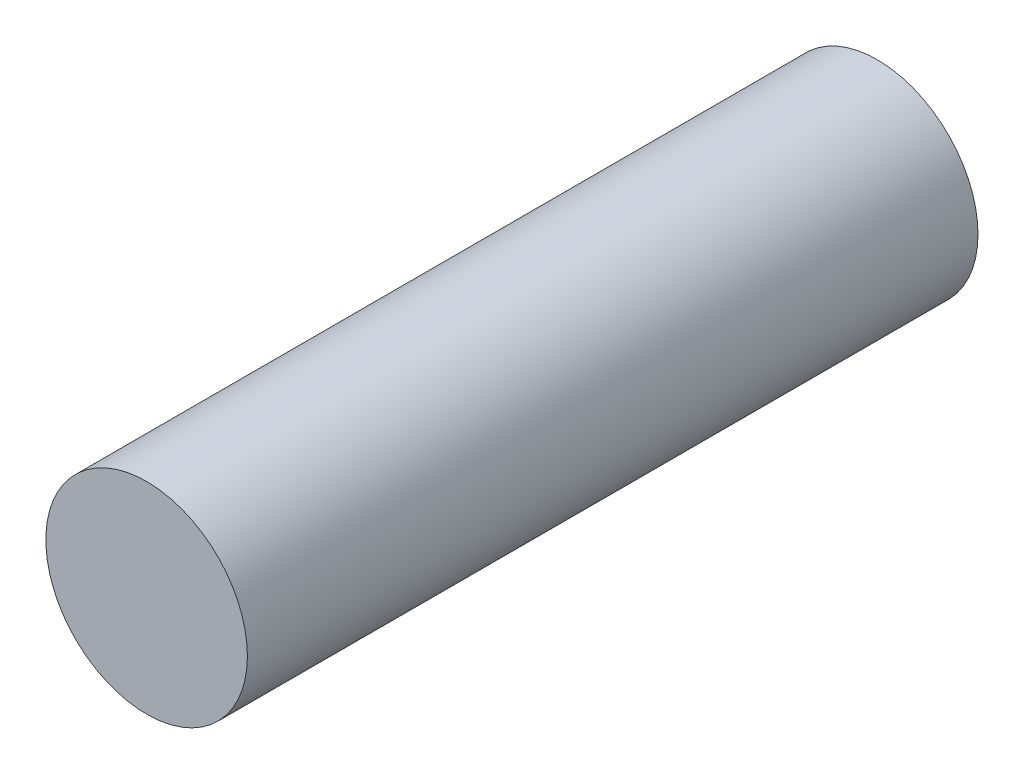
SolidWorks part; units mm, degrees
ref_plane "Plan de face" through (0, 0, 0) normal (0, 0, 1) x (1, 0, 0)
ref_plane "Plan de dessus" through (0, 0, 0) normal (0, 1, 0) x (1, 0, 0)
ref_plane "Plan de droite" through (0, 0, 0) normal (1, 0, 0) x (0, 0, -1)
sketch "Esquisse1" plane through (0, 0, 0) normal (0, 0, 1) x (1, 0, 0)
  circle A0 centre (0, 0) radius 4
  dimension "D1" = 8
extrude "Boss.-Extru.1" add sketch "Esquisse1" along normal blind 29 contours A0
